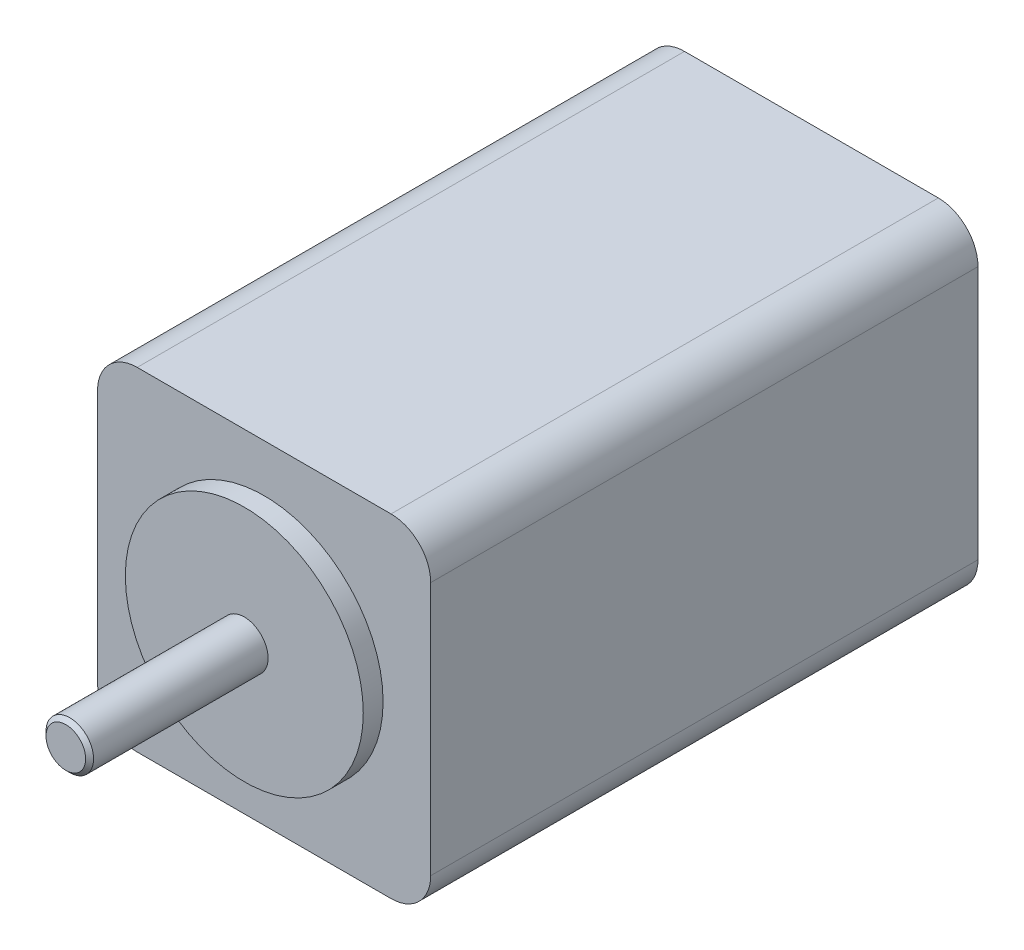
SolidWorks part; units mm, degrees
ref_plane "Front Plane" through (0, 0, 0) normal (0, 0, 1) x (1, 0, 0)
ref_plane "Top Plane" through (0, 0, 0) normal (0, 1, 0) x (1, 0, 0)
ref_plane "Right Plane" through (0, 0, 0) normal (1, 0, 0) x (0, 0, -1)
sketch "Sketch1" plane through (0, 0, 0) normal (0, 0, 1) x (1, 0, 0)
  line L1 (-21, 21) -> (21, 21)
  line L2 (-21, 21) -> (-21, -21)
  line L3 (-21, -21) -> (21, -21)
  line L4 (21, 21) -> (21, -21)
  line L5 (-21, 21) -> (21, -21) construction
  line L6 (-21, -21) -> (21, 21) construction
  point P0 (0, 0)
  dimension "D1" = 42
  dimension "D2" = 42
extrude "Boss-Extrude1" add sketch "Sketch1" along normal blind 5
fillet "Fillet1" radius 5 4 edges at (21, -21, 2.5) (-21, -21, 2.5) (-21, 21, 2.5) (21, 21, 2.5)
sketch "Sketch2" plane through (0, 0, 5) normal (0, 0, 1) x (1, 0, 0)
  circle A0 centre (0, 0) radius 15
  dimension "D1" = 30
  dimension "D2" = 0
extrude "Boss-Extrude2" add sketch "Sketch2" along normal blind 2.5
sketch "Sketch3" plane through (0, 0, 7.5) normal (0, 0, 1) x (1, 0, 0)
  circle A0 centre (0, 0) radius 3
  circle A1 centre (0, 0) radius 15 construction
  dimension "D1" = 6
  dimension "D2" = 0
extrude "Boss-Extrude3" add sketch "Sketch3" along normal blind 22.5
sketch "Sketch4" plane through (0, 0, 0) normal (0, 0, -1) x (-1, 0, 0)
  line L0 (-21, -16) -> (-21, 16) construction
  line L1 (-16, 21) -> (16, 21) construction
  line L2 (21, 16) -> (21, -16) construction
  line L3 (16, -21) -> (-16, -21) construction
  line L4 (-21, -16) -> (-21, 16)
  line L5 (-16, 21) -> (16, 21)
  line L6 (21, 16) -> (21, -16)
  line L7 (16, -21) -> (-16, -21)
  arc A0 (-16, 21) -> (-21, 16) centre (-16, 16) ccw construction
  arc A1 (21, 16) -> (16, 21) centre (16, 16) ccw construction
  arc A2 (16, -21) -> (21, -16) centre (16, -16) ccw construction
  arc A3 (-21, -16) -> (-16, -21) centre (-16, -16) ccw construction
  arc A4 (-16, 21) -> (-21, 16) centre (-16, 16) ccw
  arc A5 (21, 16) -> (16, 21) centre (16, 16) ccw
  arc A6 (16, -21) -> (21, -16) centre (16, -16) ccw
  arc A7 (-21, -16) -> (-16, -21) centre (-16, -16) ccw
  point P0 (0, 0)
  point P21 (5.1048, -3.9817)
extrude "Boss-Extrude5" add sketch "Sketch4" along normal blind 64
chamfer "Chamfer1" distance 0.5 angle 45 1 edges at (3, 0, 30)
